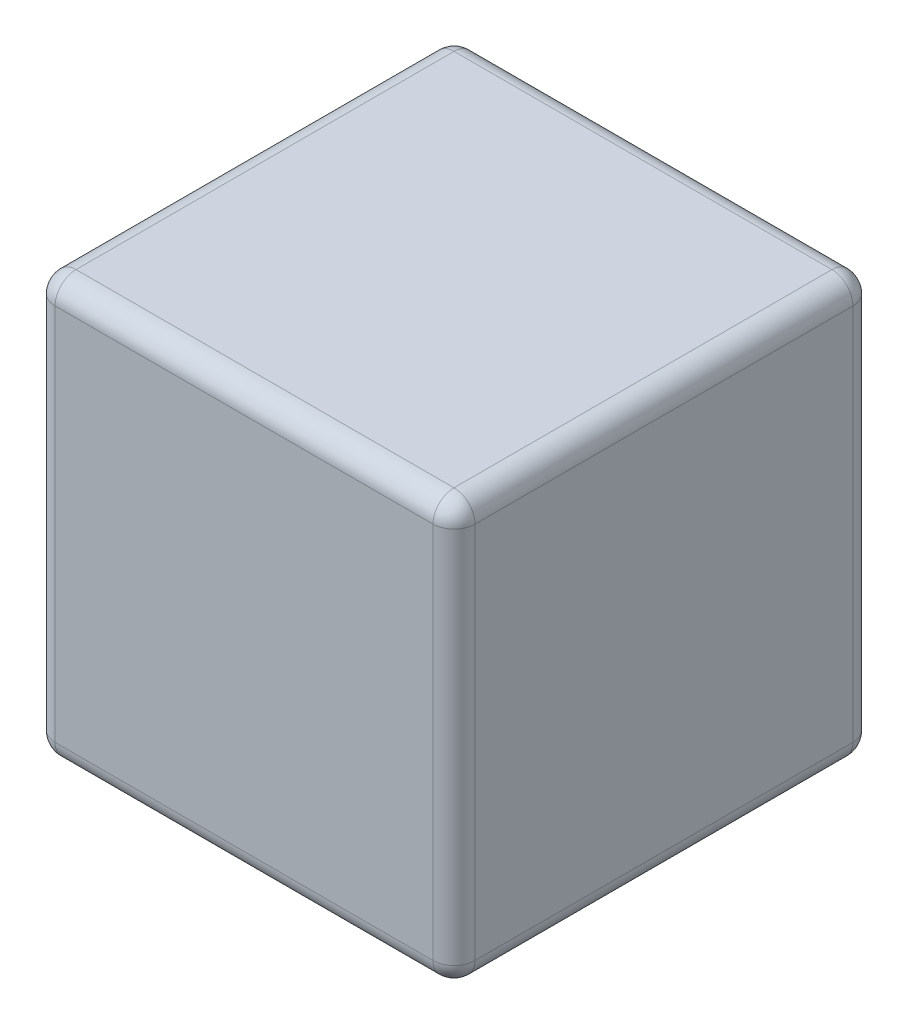
SolidWorks part; units mm, degrees
ref_plane "Front Plane" through (0, 0, 0) normal (0, 0, 1) x (1, 0, 0)
ref_plane "Top Plane" through (0, 0, 0) normal (0, 1, 0) x (1, 0, 0)
ref_plane "Right Plane" through (0, 0, 0) normal (1, 0, 0) x (0, 0, -1)
sketch "Sketch1" plane through (0, 0, 0) normal (0, 0, 1) x (1, 0, 0)
  line L1 (-20, 20) -> (20, 20)
  line L2 (-20, 20) -> (-20, -20)
  line L3 (-20, -20) -> (20, -20)
  line L4 (20, 20) -> (20, -20)
  line L5 (-20, 20) -> (20, -20) construction
  line L6 (-20, -20) -> (20, 20) construction
  point P0 (0, 0)
  dimension "D1" = 40
  dimension "D2" = 40
extrude "Boss-Extrude1" add sketch "Sketch1" along normal blind 40
fillet "Fillet1" radius 2 12 edges at (20, -20, 20) (20, 20, 20) (0, -20, 40) (0, 20, 40) (20, 0, 40) (-20, 20, 20) (-20, 0, 40) (-20, -20, 20) (0, 20, 0) (-20, 0, 0) (0, -20, 0) (20, 0, 0)
